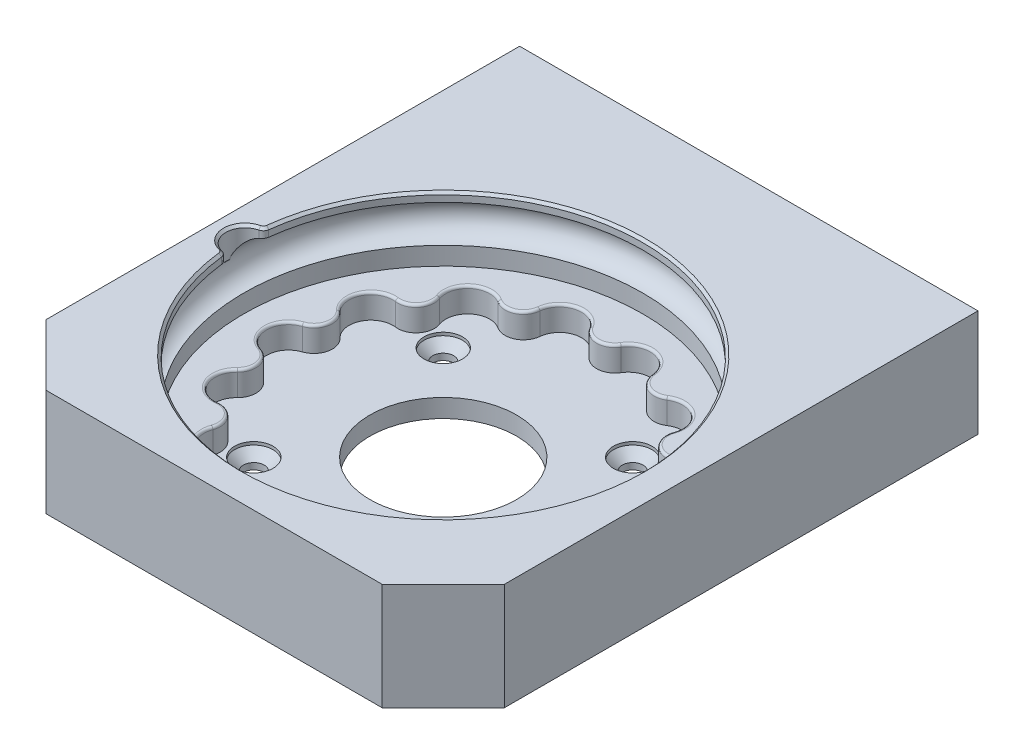
SolidWorks part; units mm, degrees
ref_plane "Front Plane" through (0, 0, 0) normal (0, 0, 1) x (1, 0, 0)
ref_plane "Top Plane" through (0, 0, 0) normal (0, 1, 0) x (1, 0, 0)
ref_plane "Right Plane" through (0, 0, 0) normal (1, 0, 0) x (0, 0, -1)
sketch "Sketch1" plane through (0, 0, 0) normal (0, 1, 0) x (1, 0, 0)
  line L0 (0, 0) -> (7.6226, 33.3969) construction
  line L1 (-37.5, -37.5) -> (37.5, -37.5)
  line L2 (-37.5, -37.5) -> (-37.5, 37.5)
  line L3 (-37.5, 37.5) -> (37.5, 37.5)
  line L4 (37.5, -37.5) -> (37.5, 37.5)
  line L5 (-37.5, -37.5) -> (37.5, 37.5) construction
  line L6 (-37.5, 37.5) -> (37.5, -37.5) construction
  circle A0 centre (0, 0) radius 28.1 construction
  circle A1 centre (0, 28.1) radius 3
  circle A2 centre (12.1921, 25.3172) radius 3
  circle A3 centre (21.9695, 17.5201) radius 3
  circle A4 centre (27.3955, 6.2528) radius 3
  circle A5 centre (27.3955, -6.2528) radius 3
  circle A6 centre (21.9695, -17.5201) radius 3
  circle A7 centre (12.1921, -25.3172) radius 3
  circle A8 centre (0, -28.1) radius 3
  circle A9 centre (-12.1921, -25.3172) radius 3
  circle A10 centre (-21.9695, -17.5201) radius 3
  circle A11 centre (-27.3955, -6.2528) radius 3
  circle A12 centre (-27.3955, 6.2528) radius 3
  circle A13 centre (-21.9695, 17.5201) radius 3
  circle A15 centre (-12.1921, 25.3172) radius 3
  arc A16 (2.5611, 26.5377) -> (9.2068, 25.0208) centre (5.6298, 24.6657) cw
  arc A17 (13.8217, 22.7984) -> (19.1512, 18.5483) centre (15.7743, 19.7803) cw
  arc A18 (22.3448, 14.5436) -> (25.3024, 8.4021) centre (22.7945, 10.9773) cw
  arc A19 (26.4422, 3.4083) -> (26.4422, -3.4083) centre (25.3, 0) cw
  arc A20 (25.3024, -8.4021) -> (22.3448, -14.5436) centre (22.7945, -10.9773) cw
  arc A21 (19.1512, -18.5483) -> (13.8217, -22.7984) centre (15.7743, -19.7803) cw
  arc A22 (9.2068, -25.0208) -> (2.5611, -26.5377) centre (5.6298, -24.6657) cw
  arc A23 (-2.5611, -26.5377) -> (-9.2068, -25.0208) centre (-5.6298, -24.6657) cw
  arc A24 (-13.8217, -22.7984) -> (-19.1512, -18.5483) centre (-15.7743, -19.7803) cw
  arc A25 (-22.3448, -14.5436) -> (-25.3024, -8.4021) centre (-22.7945, -10.9773) cw
  arc A26 (-26.4422, -3.4083) -> (-26.4422, 3.4083) centre (-25.3, 0) cw
  arc A27 (-25.3024, 8.4021) -> (-22.3448, 14.5436) centre (-22.7945, 10.9773) cw
  arc A28 (-19.1512, 18.5483) -> (-13.8217, 22.7984) centre (-15.7743, 19.7803) cw
  arc A29 (-9.2068, 25.0208) -> (-2.5611, 26.5377) centre (-5.6298, 24.6657) cw
  circle A30 centre (0, 0) radius 4.1
  circle A31 centre (0, 0) radius 25.3 construction
  point P0 (0, 0)
  point P46 (6.4297, 28.1702)
  dimension "D1" = 56.2
  dimension "D2" = 6
  dimension "D8" = 8.2
  dimension "D4" = 75
  dimension "D5" = 75
  dimension "D6" = 2.8
  dimension "D3" = 14
  dimension "D7" = 14
sketch "Sketch3" plane through (0, 0, 0) normal (0, 1, 0) x (1, 0, 0)
  line L1 (-37.5, -37.5) -> (37.5, -37.5)
  line L2 (-37.5, -37.5) -> (-37.5, 37.5)
  line L3 (-37.5, 37.5) -> (37.5, 37.5)
  line L4 (37.5, -37.5) -> (37.5, 37.5)
  line L5 (-37.5, -37.5) -> (37.5, 37.5) construction
  line L6 (-37.5, 37.5) -> (37.5, -37.5) construction
  circle A0 centre (0, 0) radius 4.1 construction
  circle A1 centre (0, 0) radius 4.1
  point P0 (0, 0)
extrude "Boss-Extrude1" add sketch "Sketch3" along normal blind 3
sketch "Sketch4" plane through (0, 3, 0) normal (0, 1, 0) x (1, 0, 0)
  line L4 (37.5, -37.5) -> (37.5, 37.5)
  line L5 (37.5, 37.5) -> (-37.5, 37.5)
  line L6 (-37.5, 37.5) -> (-37.5, -37.5)
  line L7 (-37.5, -37.5) -> (37.5, -37.5)
  line L8 (37.5, -37.5) -> (37.5, 37.5)
  line L9 (37.5, 37.5) -> (-37.5, 37.5)
  line L10 (-37.5, 37.5) -> (-37.5, -37.5)
  line L11 (-37.5, -37.5) -> (37.5, -37.5)
  line L12 (-37.5, -37.5) -> (37.5, -37.5)
  line L13 (37.5, -37.5) -> (37.5, 37.5)
  line L14 (37.5, 37.5) -> (-37.5, 37.5)
  line L15 (-37.5, 37.5) -> (-37.5, -37.5)
  line L16 (-37.5, -37.5) -> (37.5, -37.5)
  line L17 (37.5, -37.5) -> (37.5, 37.5)
  line L18 (37.5, 37.5) -> (-37.5, 37.5)
  line L19 (-37.5, 37.5) -> (-37.5, -37.5)
  arc A0 (26.4422, -3.4083) -> (26.4422, 3.4083) centre (25.3, 0) ccw construction
  circle A1 centre (27.3955, -6.2528) radius 3
  circle A2 centre (27.3955, -6.2528) radius 3
  circle A3 centre (12.1921, 25.3172) radius 3
  circle A4 centre (12.1921, 25.3172) radius 3
  circle A5 centre (0, 28.1) radius 3
  circle A6 centre (0, 28.1) radius 3
  circle A7 centre (-27.3955, 6.2528) radius 3
  circle A8 centre (-27.3955, 6.2528) radius 3
  circle A9 centre (-27.3955, -6.2528) radius 3
  circle A10 centre (-27.3955, -6.2528) radius 3
  circle A11 centre (-21.9695, -17.5201) radius 3
  circle A12 centre (-21.9695, -17.5201) radius 3
  circle A13 centre (-12.1921, -25.3172) radius 3
  circle A14 centre (-12.1921, -25.3172) radius 3
  circle A15 centre (0, -28.1) radius 3
  circle A16 centre (0, -28.1) radius 3
  circle A17 centre (12.1921, -25.3172) radius 3
  circle A18 centre (12.1921, -25.3172) radius 3
  circle A19 centre (21.9695, -17.5201) radius 3
  circle A20 centre (21.9695, -17.5201) radius 3
  circle A21 centre (27.3955, 6.2528) radius 3
  circle A22 centre (27.3955, 6.2528) radius 3
  circle A23 centre (21.9695, 17.5201) radius 3
  circle A24 centre (21.9695, 17.5201) radius 3
  circle A25 centre (0, 0) radius 4.1
  circle A26 centre (0, 0) radius 4.1
  circle A27 centre (-12.1921, 25.3172) radius 3
  circle A28 centre (-12.1921, 25.3172) radius 3
  circle A29 centre (-21.9695, 17.5201) radius 3
  circle A30 centre (-21.9695, 17.5201) radius 3
  arc A31 (25.3024, 8.4021) -> (22.3448, 14.5436) centre (22.7945, 10.9773) ccw construction
  arc A32 (19.1512, 18.5483) -> (13.8217, 22.7984) centre (15.7743, 19.7803) ccw construction
  arc A33 (9.2068, 25.0208) -> (2.5611, 26.5377) centre (5.6298, 24.6657) ccw construction
  arc A34 (-19.1512, -18.5483) -> (-13.8217, -22.7984) centre (-15.7743, -19.7803) ccw construction
  arc A35 (-9.2068, -25.0208) -> (-2.5611, -26.5377) centre (-5.6298, -24.6657) ccw construction
  arc A36 (2.5611, -26.5377) -> (9.2068, -25.0208) centre (5.6298, -24.6657) ccw construction
  arc A37 (13.8217, -22.7984) -> (19.1512, -18.5483) centre (15.7743, -19.7803) ccw construction
  arc A38 (22.3448, -14.5436) -> (25.3024, -8.4021) centre (22.7945, -10.9773) ccw construction
  arc A39 (-2.5611, 26.5377) -> (-9.2068, 25.0208) centre (-5.6298, 24.6657) ccw construction
  arc A40 (-13.8217, 22.7984) -> (-19.1512, 18.5483) centre (-15.7743, 19.7803) ccw construction
  arc A41 (-22.3448, 14.5436) -> (-25.3024, 8.4021) centre (-22.7945, 10.9773) ccw construction
  arc A42 (-26.4422, 3.4083) -> (-26.4422, -3.4083) centre (-25.3, 0) ccw construction
  arc A43 (-25.3024, -8.4021) -> (-22.3448, -14.5436) centre (-22.7945, -10.9773) ccw construction
  arc A44 (26.4422, -3.4083) -> (26.4422, 3.4083) centre (25.3, 0) ccw
  arc A45 (25.3024, 8.4021) -> (22.3448, 14.5436) centre (22.7945, 10.9773) ccw
  arc A46 (19.1512, 18.5483) -> (13.8217, 22.7984) centre (15.7743, 19.7803) ccw
  arc A47 (9.2068, 25.0208) -> (2.5611, 26.5377) centre (5.6298, 24.6657) ccw
  arc A48 (-19.1512, -18.5483) -> (-13.8217, -22.7984) centre (-15.7743, -19.7803) ccw
  arc A49 (-9.2068, -25.0208) -> (-2.5611, -26.5377) centre (-5.6298, -24.6657) ccw
  arc A50 (2.5611, -26.5377) -> (9.2068, -25.0208) centre (5.6298, -24.6657) ccw
  arc A51 (13.8217, -22.7984) -> (19.1512, -18.5483) centre (15.7743, -19.7803) ccw
  arc A52 (22.3448, -14.5436) -> (25.3024, -8.4021) centre (22.7945, -10.9773) ccw
  arc A53 (-2.5611, 26.5377) -> (-9.2068, 25.0208) centre (-5.6298, 24.6657) ccw
  arc A54 (-13.8217, 22.7984) -> (-19.1512, 18.5483) centre (-15.7743, 19.7803) ccw
  arc A55 (-22.3448, 14.5436) -> (-25.3024, 8.4021) centre (-22.7945, 10.9773) ccw
  arc A56 (-26.4422, 3.4083) -> (-26.4422, -3.4083) centre (-25.3, 0) ccw
  arc A57 (-25.3024, -8.4021) -> (-22.3448, -14.5436) centre (-22.7945, -10.9773) ccw
  line M24 (37.5, -37.5) -> (37.5, 37.5)
  line M25 (37.5, 37.5) -> (-37.5, 37.5)
  line M26 (-37.5, 37.5) -> (-37.5, -37.5)
  line M27 (-37.5, -37.5) -> (37.5, -37.5)
  dimension "D1" = 0
  dimension "D2" = 0
  dimension "D3" = 0
  dimension "D4" = 0
  dimension "D5" = 0
  dimension "D6" = 0
  dimension "D7" = 0
  dimension "D8" = 0
  dimension "D9" = 0
  dimension "D10" = 0
  dimension "D11" = 0
  dimension "D12" = 0
  dimension "D13" = 0
  dimension "D14" = 0
  dimension "D15" = 0
  dimension "D16" = 0
  dimension "D17" = 0
extrude "Boss-Extrude2" add sketch "Sketch4" along normal blind 4 contours A57 A10 A56 A8 A55 A30 A54 A28 A53 A6 A47 A4 A46 A24 A45 A22 A44 A2 A52 A20 A51 A18 A50 A16 A49 A14 A48 A12 M27 M24 M25 M26 | A24 | A22 | A2 | A20 | A18 | A16 | A14 | A12 | A10 | A8 | A30 | A28 | A6 | A4
sketch "Sketch5" plane through (0, 7, 0) normal (0, 1, 0) x (1, 0, 0)
  line L4 (-37.5, -37.5) -> (37.5, -37.5)
  line L5 (37.5, -37.5) -> (37.5, 37.5)
  line L6 (37.5, 37.5) -> (-37.5, 37.5)
  line L7 (-37.5, 37.5) -> (-37.5, -37.5)
  line L8 (-37.5, -37.5) -> (37.5, -37.5)
  line L9 (37.5, -37.5) -> (37.5, 37.5)
  line L10 (37.5, 37.5) -> (-37.5, 37.5)
  line L11 (-37.5, 37.5) -> (-37.5, -37.5)
  circle A0 centre (0, 0) radius 32.65
  circle A1 centre (-32.65, 0) radius 3.05 construction
  circle A2 centre (0, 0) radius 29.6 construction
  dimension "D2" = 65.3
  dimension "D3" = 6.1
  dimension "D4" = 1.8
  dimension "D1" = 0
extrude "Boss-Extrude3" add sketch "Sketch5" along normal blind 10.5
sketch "Sketch7" plane through (0, 3, 0) normal (0, 1, 0) x (1, 0, 0)
  line L1 (-12.0018, -12.0018) -> (12.0018, -12.0018) construction
  line L2 (-12.0018, -12.0018) -> (-12.0018, 12.0018) construction
  line L3 (-12.0018, 12.0018) -> (12.0018, 12.0018) construction
  line L4 (12.0018, -12.0018) -> (12.0018, 12.0018) construction
  line L5 (-12.0018, -12.0018) -> (12.0018, 12.0018) construction
  line L6 (-12.0018, 12.0018) -> (12.0018, -12.0018) construction
  point P0 (0, 0)
sketch "Sketch8" plane through (0, 17.5, 0) normal (0, 1, 0) x (1, 0, 0)
  line L0 (37.5, 15.533) -> (15.533, 37.5)
  line L1 (-15.533, 37.5) -> (-37.5, 15.533)
  line L2 (-37.5, 15.533) -> (-37.5, -15.533)
  line L3 (-37.5, -15.533) -> (-15.533, -37.5)
  line L4 (-15.533, -37.5) -> (15.533, -37.5)
  line L5 (15.533, -37.5) -> (37.5, -15.533)
  line L6 (37.5, -15.533) -> (37.5, 15.533)
  line L7 (15.533, 37.5) -> (-15.533, 37.5)
  line L8 (-37.5, 37.5) -> (-37.5, -37.5) construction
  circle A0 centre (0, 0) radius 37.5 construction
extrude "Cut-Extrude1" [suppressed] cut sketch "Sketch8" against normal through all flip side to cut
chamfer "Chamfer1" distance 10 angle 45 2 edges at (37.5, 8.75, 37.5) (-37.5, 8.75, 37.5)
sketch "Sketch11" plane through (0, 0, 0) normal (0, 0, 1) x (1, 0, 0)
  line L1 (32.65, 17.5) -> (-32.65, 17.5) construction
  line L4 (0, 0) -> (0, 37.5091) construction
  circle A0 centre (-32.45, 13) radius 3.05
  dimension "D1" = 6.1
  dimension "D2" = 4.5
  dimension "D3" = 64.9
revolve "Cut-Revolve1" cut sketch "Sketch11" angle 360 about L4
sketch "Sketch12" plane through (0, 17.5, 0) normal (0, 1, 0) x (1, 0, 0)
  line L0 (-32.45, 0) -> (0, 0) construction
  line L1 (-35.5, 0) -> (-29.4, 0) construction
  circle A0 centre (-32.45, 0) radius 3.1
  dimension "D1" = 6.2
extrude "Cut-Extrude2" cut sketch "Sketch12" against normal up to vertex (39.8753 mm away)
fillet "Fillet2" radius 1 2 edges at (-32.5025, 16.7717, 3.0996) (-32.5025, 16.7717, -3.0996)
sketch "Sketch14" plane through (0, 0, 0) normal (0, -1, 0) x (1, 0, 0)
  line L1 (-15.5, -15.5) -> (15.5, -15.5) construction
  line L2 (-15.5, -15.5) -> (-15.5, 15.5) construction
  line L3 (-15.5, 15.5) -> (15.5, 15.5) construction
  line L4 (15.5, -15.5) -> (15.5, 15.5) construction
  line L5 (-15.5, -15.5) -> (15.5, 15.5) construction
  line L6 (-15.5, 15.5) -> (15.5, -15.5) construction
  circle A0 centre (0, 0) radius 12
  circle A1 centre (-15.5, 15.5) radius 3.3155 construction
  circle A2 centre (15.5, 15.5) radius 2.5111 construction
  circle A3 centre (15.5, -15.5) radius 2.6783 construction
  circle A4 centre (-15.5, -15.5) radius 2.6959 construction
  dimension "D2" = 24
  dimension "D1" = 31
extrude "Cut-Extrude3" cut sketch "Sketch14" against normal through all
hole_wizard "CSK for M3 Countersunk Flat Head Screw1" positions "Sketch15" profile "Sketch16" countersink size "M3" standard "ISO" end condition through all
sketch "Sketch15" plane through (0, 3, 0) normal (0, 1, 0) x (1, 0, 0)
  point P0 (-15.5, 15.5)
  point P3 (15.5, 15.5)
  point P6 (15.5, -15.5)
  point P9 (-15.5, -15.5)
sketch "Sketch16" plane through (-15.5, 3, -15.5) normal (1, 0, 0) x (0, 0, 1)
  line L0 (0, 0) -> (0, 3)
  line L1 (0, 3) -> (1.7, 3)
  line L2 (1.7, 3) -> (1.7, 1.95)
  line L3 (1.7, 1.95) -> (3.15, 0.5)
  line L4 (3.15, 0.5) -> (3.15, 0)
  line L6 (3.15, 0) -> (0, 0)
  line L7 (-1.7, 1.95) -> (-3.15, 0.5) construction
  line L11 (0, -6.35) -> (0, 107.95) construction
  dimension "Thru Hole Dia." = 3.4
  dimension "Thru Hole Depth" = 3
  dimension "C'Sink Dia." = 6.3
  dimension "C'Sink Angle" = 90
  dimension "Head Clearance" = 0.5
chamfer "Chamfer2" distance 0.4 angle 45 4 edges at (-35.55, 17.5, 0) (-32.6655, 17.5, 3.3212) (-32.6655, 17.5, -3.3212) (32.65, 17.5, 0)
fillet "Fillet3" radius 0.4 28 edges at (-26.0332, 7, 12.5369) (-19.624, 7, 15.6496) (-18.0155, 7, 22.5907) (-10.8905, 7, 22.6143) (-6.4297, 7, 28.1702) (0, 7, 25.1) (6.4297, 7, 28.1702) (10.8905, 7, 22.6143) (18.0155, 7, 22.5907) (19.624, 7, 15.6496) (26.0332, 7, 12.5369) (24.4707, 7, 5.5853) (28.8946, 7, 0) (24.4707, 7, -5.5853) (26.0332, 7, -12.5369) (19.624, 7, -15.6496) (18.0155, 7, -22.5907) (10.8905, 7, -22.6143) (6.4297, 7, -28.1702) (0, 7, -25.1) (-6.4297, 7, -28.1702) (-10.8905, 7, -22.6143) (-18.0155, 7, -22.5907) (-19.624, 7, -15.6496) (-26.0332, 7, -12.5369) (-24.4707, 7, -5.5853) (-28.8946, 7, 0) (-24.4707, 7, 5.5853)
sketch "Sketch17" plane through (0, 0, -37.5) normal (0, 0, -1) x (-1, 0, 0)
  line L4 (-37.5, 0) -> (37.5, 0)
  line L5 (37.5, 0) -> (37.5, 17.5)
  line L6 (37.5, 17.5) -> (-37.5, 17.5)
  line L7 (-37.5, 17.5) -> (-37.5, 0)
  line L8 (-37.5, 0) -> (37.5, 0)
  line L9 (37.5, 0) -> (37.5, 17.5)
  line L10 (37.5, 17.5) -> (-37.5, 17.5)
  line L11 (-37.5, 17.5) -> (-37.5, 0)
  dimension "D1" = 0
extrude "Boss-Extrude4" add sketch "Sketch17" along normal blind 12.5
sketch "Sketch19" plane through (0, 0, -50) normal (0, 0, -1) x (-1, 0, 0)
  line L0 (0, 0) -> (0, 11.3428) construction
  line L1 (-37.5, 0) -> (37.5, 0) construction
  line L2 (37.5, 17.5) -> (-37.5, 17.5) construction
  circle A0 centre (29, 9) radius 2.9
  circle A1 centre (-29, 9) radius 2.9
  dimension "D1" = 8.5
  dimension "D2" = 58
  dimension "D3" = 5.8
extrude "Cut-Extrude4" cut sketch "Sketch19" against normal blind 6.5
hole_wizard "M4 Clearance Hole1" positions "Sketch22" profile "Sketch23" hole size "M4" standard "ISO"
sketch "Sketch22" plane through (0, 0, -50) normal (0, 0, -1) x (-1, 0, 0)
  point P0 (29, 9)
  point P3 (-29, 9)
sketch "Sketch23" plane through (-29, 9, -50) normal (1, 0, 0) x (0, 1, 0)
  line L0 (0, 0) -> (0, 11.3519)
  line L1 (0, 11.3519) -> (2.25, 10)
  line L2 (2.25, 10) -> (2.25, 0)
  line L5 (2.25, 0) -> (0, 0)
  line L10 (0, 11.3519) -> (-2.25, 10) construction
  line L11 (0, -6.35) -> (0, 107.95) construction
  dimension "Hole Dia." = 4.5
  dimension "Hole Depth" = 10
  dimension "Drill Angle" = 118
equation "\"N\"= 14"
equation "\"Rr\"= 3"
equation "\"R\"= 28.1"
equation "\"E\"= 1.5"
equation "\"D3@Sketch1\"=\"N\""
equation "\"D1@Sketch1\"=\"R\" *2"
equation "\"D2@Sketch1\"=\"Rr\" *2"
